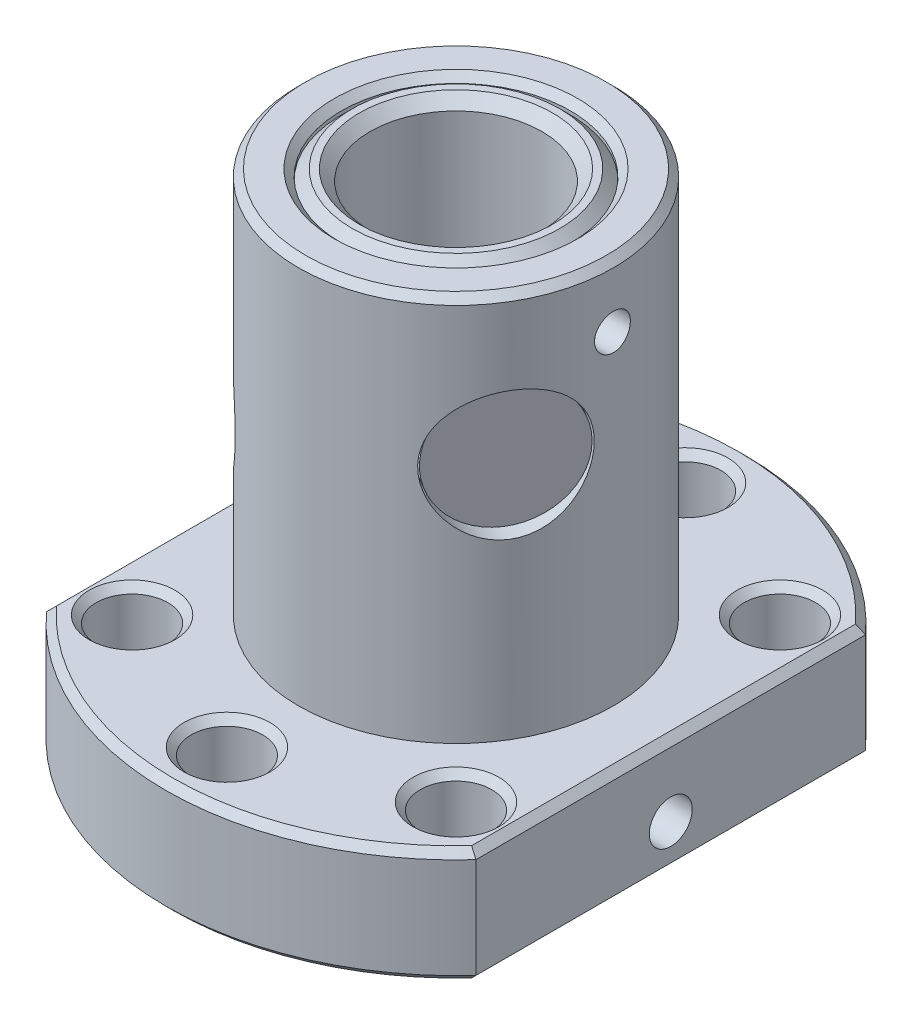
SolidWorks part; units mm, degrees
ref_plane "Front" through (0, 0, 0) normal (0, 0, 1) x (1, 0, 0)
ref_plane "Top" through (0, 0, 0) normal (0, 1, 0) x (1, 0, 0)
ref_plane "Right" through (0, 0, 0) normal (1, 0, 0) x (0, 0, -1)
sketch "Sketch1" plane through (0, 0, 0) normal (0, 1, 0) x (1, 0, 0)
  line L0 (0, 20.25) -> (0, -20.25) construction
  line L1 (-15, 0) -> (15, 0) construction
  line L2 (-15, 13.6038) -> (-15, -13.6038)
  line L3 (15, 13.6038) -> (15, -13.6038)
  arc A0 (-15, -13.6038) -> (15, -13.6038) centre (0, 0) ccw
  arc A1 (15, 13.6038) -> (-15, 13.6038) centre (0, 0) ccw
  dimension "D1" = 40.5
  dimension "D2" = 30
extrude "Boss-Extrude1" add sketch "Sketch1" along normal blind 8
sketch "Sketch2" plane through (0, 8, 0) normal (0, 1, 0) x (1, 0, 0)
  circle A0 centre (0, 0) radius 11
  dimension "D1" = 22
extrude "Boss-Extrude2" add sketch "Sketch2" along normal blind 27
hole_wizard "Ø16.0mm Dowel Hole1" positions "Sketch4" profile "Sketch5" hole size "Ø16.0" standard "ISO" end condition through all
sketch "Sketch4" plane through (0, 0, 0) normal (0, -1, 0) x (-1, 0, 0)
  point P0 (0, 0)
sketch "Sketch5" plane through (0, 0, 0) normal (1, 0, 0) x (0, 0, -1)
  line L0 (0, 0) -> (0, 35)
  line L1 (0, 35) -> (8, 35)
  line L2 (8, 35) -> (8, 0)
  line L5 (8, 0) -> (0, 0)
  line L11 (0, -6.35) -> (0, 107.95) construction
  dimension "Thru Hole Dia." = 16
  dimension "Thru Hole Depth" = 35
hole_wizard "Ø5.0mm Dowel Hole1" positions "Sketch7" profile "Sketch6" hole size "Ø5.0" standard "ISO" end condition up to next
sketch "Sketch7" plane through (0, 0, 0) normal (0, -1, 0) x (-1, 0, 0)
  line L0 (0, -20.25) -> (0, 20.25) construction
  line L2 (15, 0) -> (-15, 0) construction
  line L3 (15, 13.6038) -> (15, -13.6038) construction
  line L4 (-15, -13.6038) -> (-15, 13.6038) construction
  line L6 (0, 0) -> (11.3137, -11.3137) construction
  arc A0 (-15, -13.6038) -> (15, -13.6038) centre (0, 0) ccw construction
  arc A1 (15, 13.6038) -> (-15, 13.6038) centre (0, 0) ccw construction
  point P0 (0, -16)
  point P2 (11.3137, -11.3137)
  point P30 (-11.3137, -11.3137)
  point P32 (-11.3137, 11.3137)
  point P33 (0, 16)
  point P34 (11.3137, 11.3137)
  dimension "D1" = 16
  dimension "D2" = 45
  dimension "D3" = 16
sketch "Sketch6" plane through (0, 0, 16) normal (1, 0, 0) x (0, 0, -1)
  line L0 (0, 0) -> (0, 8)
  line L1 (0, 8) -> (2.5, 8)
  line L2 (2.5, 8) -> (2.5, 0)
  line L5 (2.5, 0) -> (0, 0)
  line L11 (0, -6.35) -> (0, 107.95) construction
  dimension "Thru Hole Dia." = 5
  dimension "Thru Hole Depth" = 8
hole_wizard "Ø3.0mm Dowel Hole1" positions "Sketch9" profile "Sketch8" hole size "Ø3.0" standard "ISO" end condition through all
sketch "Sketch9" plane through (15, 0, 0) normal (1, 0, 0) x (0, 0, -1)
  point P0 (0, 3)
  dimension "D1" = 3
sketch "Sketch8" plane through (15, 3, 0) normal (0, 1, 0) x (0, 0, -1)
  line L0 (0, 0) -> (0, 30)
  line L1 (0, 30) -> (1.5, 30)
  line L2 (1.5, 30) -> (1.5, 0)
  line L5 (1.5, 0) -> (0, 0)
  line L11 (0, -6.35) -> (0, 107.95) construction
  dimension "Thru Hole Dia." = 3
  dimension "Thru Hole Depth" = 30
hole_wizard "M5 Tapped Hole1" positions "3DSketch1" profile "Sketch10" tap size "M5" standard "ISO"
sketch3d "3DSketch1"
  line L1 (0, 0, 0) -> (0, 0, -16) construction
  line L2 (0, 8, -16) -> (0, 0, -16) construction
  line L4 (0, 0, 0) -> (7.7493, 0, -18.7086) construction
  arc A0 (15, 0, -13.6038) -> (-15, 0, -13.6038) centre (0, 0, 0) ccw construction
  point P17 (0, 20.25, 0)
  point P40 (7.7491, 5, -18.7087)
  dimension "D1" = 22.5
  dimension "D2" = 5
sketch "Sketch10" plane through (7.7491, 5, -18.7087) normal (0, 1, 0) x (-0.9239, 0, -0.3827)
  line L0 (0, 0) -> (0, 12.25)
  line L1 (0, 12.25) -> (2.1, 12.25)
  line L2 (2.1, 12.25) -> (2.1, 0)
  line L5 (2.1, 0) -> (0, 0)
  line L11 (0, -6.35) -> (0, 16.6804) construction
  dimension "Thru Tap Drill Dia." = 4.2
  dimension "Thru Tap Drill Depth" = 12.25
cosmetic thread "Hole Thread1" parameters "D1"=6, "D2"=5
hole_wizard "Ø8.0mm Dowel Hole1" positions "3DSketch2" profile "Sketch16" hole size "Ø8.0" standard "ISO"
sketch3d "3DSketch2"
  point P10 (-9.6802, 19.8908, 5.2243)
  point P18 (9.4508, 24.6248, 5.6287)
  point P21 (1.1665, 15, -10.938)
  dimension "D1" = 7
sketch "Sketch16" plane through (-9.6802, 19.8908, 5.2243) normal (0, 1, 0) x (0.4749, 0, 0.88)
  line L0 (0, 0) -> (0, 3)
  line L1 (0, 3) -> (4.5, 3)
  line L2 (4.5, 3) -> (4.5, 0)
  line L5 (4.5, 0) -> (0, 0)
  line L11 (0, -6.35) -> (0, 107.95) construction
  dimension "Thru Hole Dia." = 9
  dimension "Thru Hole Depth" = 3
hole_wizard "M3 Tapped Hole1" positions "Sketch18" profile "Sketch19" tap size "M3" standard "ISO" end condition through all
sketch "Sketch18" plane through (-15, 0, 0) normal (1, 0, 0) x (0, 0, -1)
  point P0 (0, 30.6226)
sketch "Sketch19" plane through (-15, 30.6226, 0) normal (0, 1, 0) x (0, 0, 1)
  line L0 (0, 0) -> (0, 30)
  line L1 (0, 30) -> (1.25, 30)
  line L2 (1.25, 30) -> (1.25, 0)
  line L5 (1.25, 0) -> (0, 0)
  line L11 (0, -6.35) -> (0, 107.95) construction
  dimension "Thru Tap Drill Dia." = 2.5
  dimension "Thru Tap Drill Depth" = 30
cosmetic thread "Hole Thread3" parameters "D2"=3
sketch "Sketch20" plane through (0, 0, 0) normal (0, -1, 0) x (1, 0, 0)
  circle A0 centre (0, 0) radius 8
  circle A1 centre (0, 0) radius 6
  dimension "D1" = 16
  dimension "D2" = 12
extrude "Boss-Extrude3" add sketch "Sketch20" against normal up to surface (35 mm away) separate body up to face at (0, 35, -8)
chamfer "Chamfer1" distance 0.5 23 edges at (0, 35, 11) (0, 35, -8) (15, 8, 0) (0, 8, 20.25) (-15, 8, 0) (0, 8, -20.25) (-11.3137, 8, -8.8137) (0, 8, -13.5) (11.3137, 8, -8.8137) (11.3137, 8, 13.8137) (-11.3137, 8, 13.8137) (0, 8, 18.5) (-11.3137, 0, 8.8137) (11.3137, 0, 8.8137) (11.3137, 0, -13.8137) (0, 0, -18.5) (-11.3137, 0, -13.8137) (0, 0, -8) (-15, 0, 0) (0, 0, 20.25) (15, 0, 0) (0, 0, -20.25) (0, 0, 13.5)
chamfer "Chamfer2" distance 0.75 4 edges at (0, 35, 6) (0, 35, 8) (0, 0, -8) (0, 0, -6)
ref_plane "Plane1" through (0.8483, 0, -7.9549) normal (0.106, 0, -0.9944) x (-0.9944, 0, -0.106)
sketch "Sketch21" plane through (0.8483, 0, -7.9549) normal (0.106, 0, -0.9944) x (-0.9944, 0, -0.106)
  circle A0 centre (0, 15) radius 4.4
  dimension "D1" = 8.8
extrude "Boss-Extrude4" add sketch "Sketch21" along normal blind 2 separate body
ref_plane "Plane2" through (-7.0402, 0, 3.7995) normal (-0.88, 0, 0.4749) x (0.4749, 0, 0.88)
sketch "Sketch22" plane through (-7.0402, 0, 3.7995) normal (-0.88, 0, 0.4749) x (0.4749, 0, 0.88)
  circle A0 centre (0, 19.8908) radius 4.4
  dimension "D1" = 8.8
extrude "Boss-Extrude5" add sketch "Sketch22" along normal blind 2
ref_plane "Plane3" through (6.8733, 0, 4.0936) normal (0.8592, 0, 0.5117) x (0.5117, 0, -0.8592)
sketch "Sketch23" plane through (6.8733, 0, 4.0936) normal (0.8592, 0, 0.5117) x (0.5117, 0, -0.8592)
  circle A0 centre (0, 24.6248) radius 4.4
  dimension "D1" = 8.8
extrude "Boss-Extrude6" add sketch "Sketch23" along normal blind 2 separate body
